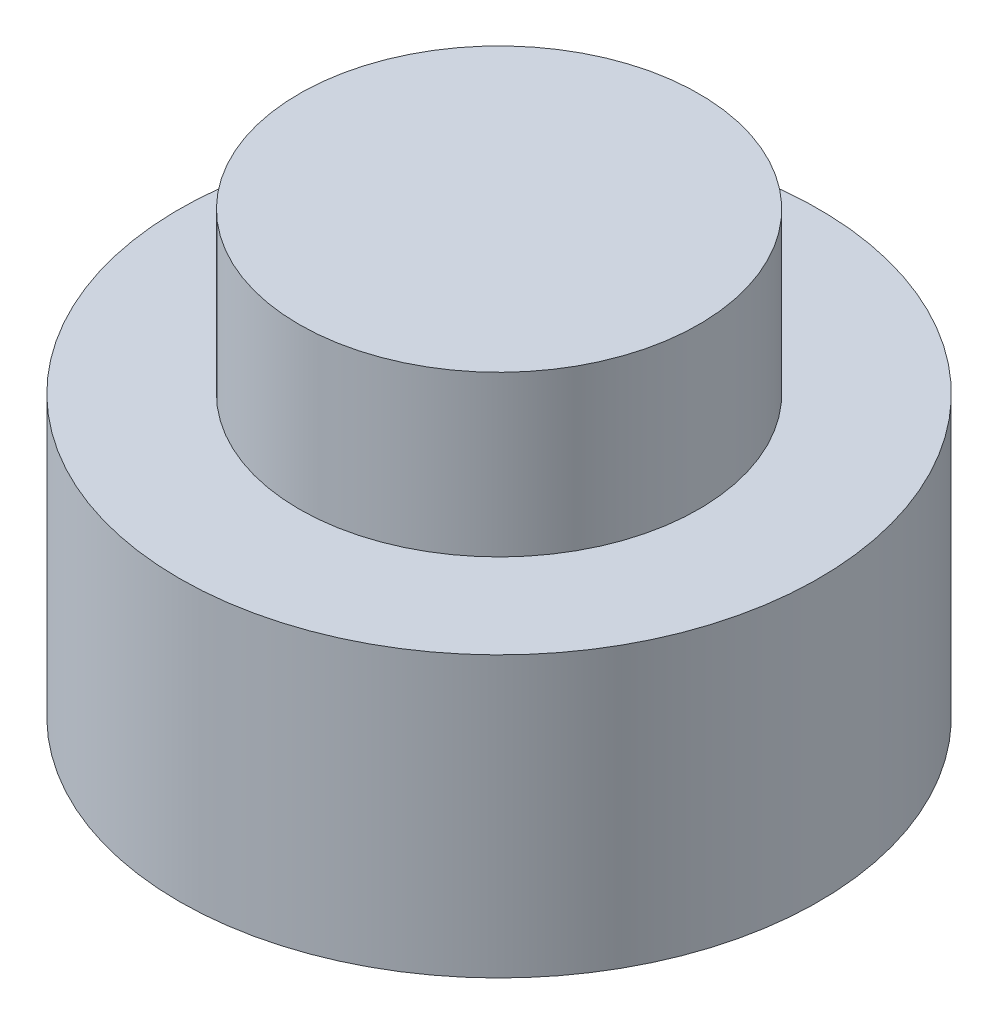
SolidWorks part; units mm, degrees
ref_plane "前视基准面" through (0, 0, 0) normal (0, 0, 1) x (1, 0, 0)
ref_plane "上视基准面" through (0, 0, 0) normal (0, 1, 0) x (1, 0, 0)
ref_plane "右视基准面" through (0, 0, 0) normal (1, 0, 0) x (0, 0, -1)
sketch "草图1" plane through (0, 0, 0) normal (0, 1, 0) x (1, 0, 0)
  circle A0 centre (0, 0) radius 8
extrude "凸台-拉伸1" add sketch "草图1" along normal blind 7
sketch "草图2" plane through (0, 7, 0) normal (0, 1, 0) x (1, 0, 0)
  circle A0 centre (0, 0) radius 5
extrude "凸台-拉伸2" add sketch "草图2" along normal blind 4
